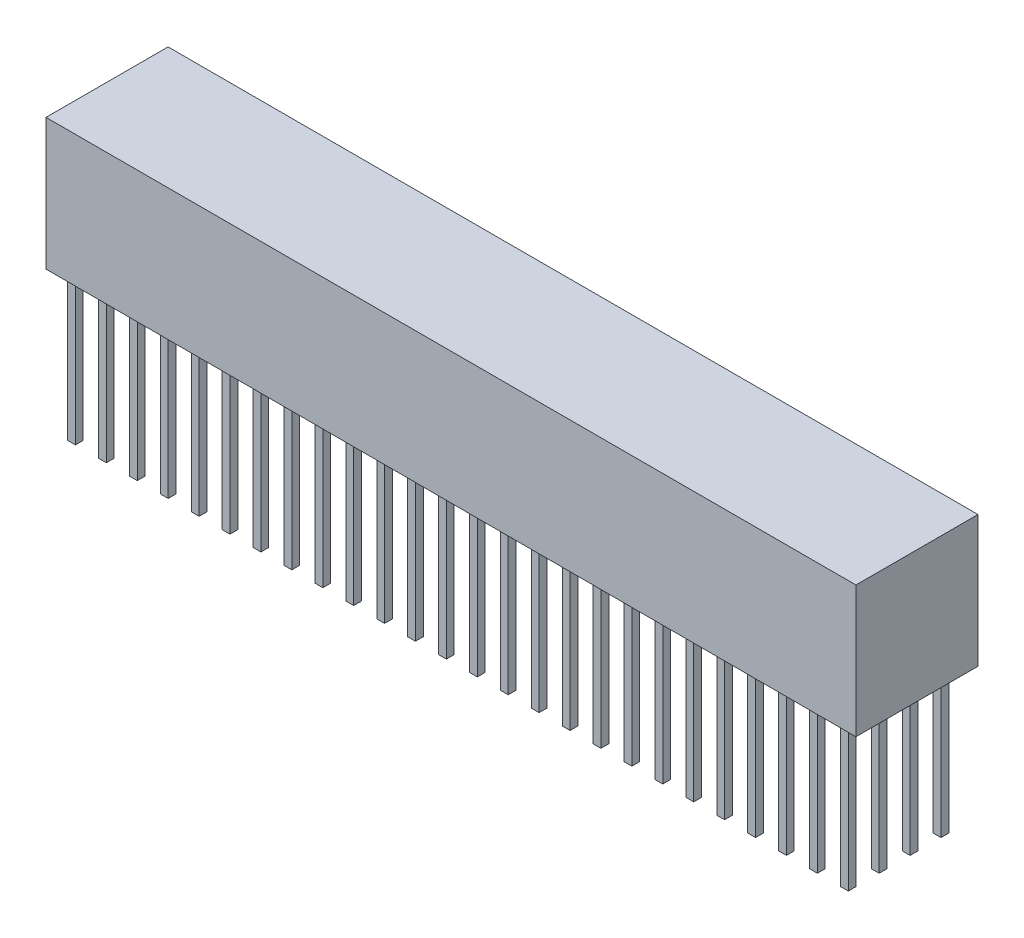
SolidWorks part; units mm, degrees
ref_plane "Front Plane" through (0, 0, 0) normal (0, 0, 1) x (1, 0, 0)
ref_plane "Top Plane" through (0, 0, 0) normal (0, 1, 0) x (1, 0, 0)
ref_plane "Right Plane" through (0, 0, 0) normal (1, 0, 0) x (0, 0, -1)
sketch "Sketch1" plane through (0, 0, 0) normal (0, 1, 0) x (1, 0, 0)
  line L1 (0, 0) -> (66.55, 0)
  line L2 (0, 0) -> (0, 10.03)
  line L3 (0, 10.03) -> (66.55, 10.03)
  line L4 (66.55, 0) -> (66.55, 10.03)
  dimension "D1" = 66.55
  dimension "D2" = 10.03
extrude "Boss-Extrude1" add sketch "Sketch1" along normal blind 10.8
sketch "Sketch2" plane through (0, 0, 0) normal (0, -1, 0) x (1, 0, 0)
  line L0 (0, 0) -> (66.55, 0) construction
  line L1 (0.89, -0.89) -> (1.53, -0.89)
  line L2 (0.89, -0.89) -> (0.89, -1.53)
  line L3 (0.89, -1.53) -> (1.53, -1.53)
  line L4 (1.53, -0.89) -> (1.53, -1.53)
  line L5 (0, -10.03) -> (0, 0) construction
  line L6 (3.43, -0.89) -> (3.43, -1.53)
  line L7 (3.43, -0.89) -> (4.07, -0.89)
  line L8 (4.07, -0.89) -> (4.07, -1.53)
  line L9 (3.43, -1.53) -> (4.07, -1.53)
  line L10 (5.97, -0.89) -> (5.97, -1.53)
  line L11 (5.97, -0.89) -> (6.61, -0.89)
  line L12 (6.61, -0.89) -> (6.61, -1.53)
  line L13 (5.97, -1.53) -> (6.61, -1.53)
  line L14 (8.51, -0.89) -> (8.51, -1.53)
  line L15 (8.51, -0.89) -> (9.15, -0.89)
  line L16 (9.15, -0.89) -> (9.15, -1.53)
  line L17 (8.51, -1.53) -> (9.15, -1.53)
  line L18 (11.05, -0.89) -> (11.05, -1.53)
  line L19 (11.05, -0.89) -> (11.69, -0.89)
  line L20 (11.69, -0.89) -> (11.69, -1.53)
  line L21 (11.05, -1.53) -> (11.69, -1.53)
  line L22 (13.59, -0.89) -> (13.59, -1.53)
  line L23 (13.59, -0.89) -> (14.23, -0.89)
  line L24 (14.23, -0.89) -> (14.23, -1.53)
  line L25 (13.59, -1.53) -> (14.23, -1.53)
  line L26 (16.13, -0.89) -> (16.13, -1.53)
  line L27 (16.13, -0.89) -> (16.77, -0.89)
  line L28 (16.77, -0.89) -> (16.77, -1.53)
  line L29 (16.13, -1.53) -> (16.77, -1.53)
  line L30 (18.67, -0.89) -> (18.67, -1.53)
  line L31 (18.67, -0.89) -> (19.31, -0.89)
  line L32 (19.31, -0.89) -> (19.31, -1.53)
  line L33 (18.67, -1.53) -> (19.31, -1.53)
  line L34 (21.21, -0.89) -> (21.21, -1.53)
  line L35 (21.21, -0.89) -> (21.85, -0.89)
  line L36 (21.85, -0.89) -> (21.85, -1.53)
  line L37 (21.21, -1.53) -> (21.85, -1.53)
  line L38 (23.75, -0.89) -> (23.75, -1.53)
  line L39 (23.75, -0.89) -> (24.39, -0.89)
  line L40 (24.39, -0.89) -> (24.39, -1.53)
  line L41 (23.75, -1.53) -> (24.39, -1.53)
  line L42 (26.29, -0.89) -> (26.29, -1.53)
  line L43 (26.29, -0.89) -> (26.93, -0.89)
  line L44 (26.93, -0.89) -> (26.93, -1.53)
  line L45 (26.29, -1.53) -> (26.93, -1.53)
  line L46 (28.83, -0.89) -> (28.83, -1.53)
  line L47 (28.83, -0.89) -> (29.47, -0.89)
  line L48 (29.47, -0.89) -> (29.47, -1.53)
  line L49 (28.83, -1.53) -> (29.47, -1.53)
  line L50 (31.37, -0.89) -> (31.37, -1.53)
  line L51 (31.37, -0.89) -> (32.01, -0.89)
  line L52 (32.01, -0.89) -> (32.01, -1.53)
  line L53 (31.37, -1.53) -> (32.01, -1.53)
  line L54 (33.91, -0.89) -> (33.91, -1.53)
  line L55 (33.91, -0.89) -> (34.55, -0.89)
  line L56 (34.55, -0.89) -> (34.55, -1.53)
  line L57 (33.91, -1.53) -> (34.55, -1.53)
  line L58 (36.45, -0.89) -> (36.45, -1.53)
  line L59 (36.45, -0.89) -> (37.09, -0.89)
  line L60 (37.09, -0.89) -> (37.09, -1.53)
  line L61 (36.45, -1.53) -> (37.09, -1.53)
  line L62 (38.99, -0.89) -> (38.99, -1.53)
  line L63 (38.99, -0.89) -> (39.63, -0.89)
  line L64 (39.63, -0.89) -> (39.63, -1.53)
  line L65 (38.99, -1.53) -> (39.63, -1.53)
  line L66 (41.53, -0.89) -> (41.53, -1.53)
  line L67 (41.53, -0.89) -> (42.17, -0.89)
  line L68 (42.17, -0.89) -> (42.17, -1.53)
  line L69 (41.53, -1.53) -> (42.17, -1.53)
  line L70 (44.07, -0.89) -> (44.07, -1.53)
  line L71 (44.07, -0.89) -> (44.71, -0.89)
  line L72 (44.71, -0.89) -> (44.71, -1.53)
  line L73 (44.07, -1.53) -> (44.71, -1.53)
  line L74 (46.61, -0.89) -> (46.61, -1.53)
  line L75 (46.61, -0.89) -> (47.25, -0.89)
  line L76 (47.25, -0.89) -> (47.25, -1.53)
  line L77 (46.61, -1.53) -> (47.25, -1.53)
  line L78 (49.15, -0.89) -> (49.15, -1.53)
  line L79 (49.15, -0.89) -> (49.79, -0.89)
  line L80 (49.79, -0.89) -> (49.79, -1.53)
  line L81 (49.15, -1.53) -> (49.79, -1.53)
  line L82 (51.69, -0.89) -> (51.69, -1.53)
  line L83 (51.69, -0.89) -> (52.33, -0.89)
  line L84 (52.33, -0.89) -> (52.33, -1.53)
  line L85 (51.69, -1.53) -> (52.33, -1.53)
  line L86 (54.23, -0.89) -> (54.23, -1.53)
  line L87 (54.23, -0.89) -> (54.87, -0.89)
  line L88 (54.87, -0.89) -> (54.87, -1.53)
  line L89 (54.23, -1.53) -> (54.87, -1.53)
  line L90 (56.77, -0.89) -> (56.77, -1.53)
  line L91 (56.77, -0.89) -> (57.41, -0.89)
  line L92 (57.41, -0.89) -> (57.41, -1.53)
  line L93 (56.77, -1.53) -> (57.41, -1.53)
  line L94 (59.31, -0.89) -> (59.31, -1.53)
  line L95 (59.31, -0.89) -> (59.95, -0.89)
  line L96 (59.95, -0.89) -> (59.95, -1.53)
  line L97 (59.31, -1.53) -> (59.95, -1.53)
  line L98 (61.85, -0.89) -> (61.85, -1.53)
  line L99 (61.85, -0.89) -> (62.49, -0.89)
  line L100 (62.49, -0.89) -> (62.49, -1.53)
  line L101 (61.85, -1.53) -> (62.49, -1.53)
  line L102 (3.43, -3.43) -> (3.43, -4.07)
  line L103 (3.43, -3.43) -> (4.07, -3.43)
  line L104 (4.07, -3.43) -> (4.07, -4.07)
  line L105 (3.43, -4.07) -> (4.07, -4.07)
  line L106 (5.97, -3.43) -> (5.97, -4.07)
  line L107 (5.97, -3.43) -> (6.61, -3.43)
  line L108 (6.61, -3.43) -> (6.61, -4.07)
  line L109 (5.97, -4.07) -> (6.61, -4.07)
  line L110 (8.51, -3.43) -> (8.51, -4.07)
  line L111 (8.51, -3.43) -> (9.15, -3.43)
  line L112 (9.15, -3.43) -> (9.15, -4.07)
  line L113 (8.51, -4.07) -> (9.15, -4.07)
  line L114 (11.05, -3.43) -> (11.05, -4.07)
  line L115 (11.05, -3.43) -> (11.69, -3.43)
  line L116 (11.69, -3.43) -> (11.69, -4.07)
  line L117 (11.05, -4.07) -> (11.69, -4.07)
  line L118 (13.59, -3.43) -> (13.59, -4.07)
  line L119 (13.59, -3.43) -> (14.23, -3.43)
  line L120 (14.23, -3.43) -> (14.23, -4.07)
  line L121 (13.59, -4.07) -> (14.23, -4.07)
  line L122 (16.13, -3.43) -> (16.13, -4.07)
  line L123 (16.13, -3.43) -> (16.77, -3.43)
  line L124 (16.77, -3.43) -> (16.77, -4.07)
  line L125 (16.13, -4.07) -> (16.77, -4.07)
  line L126 (18.67, -3.43) -> (18.67, -4.07)
  line L127 (18.67, -3.43) -> (19.31, -3.43)
  line L128 (19.31, -3.43) -> (19.31, -4.07)
  line L129 (18.67, -4.07) -> (19.31, -4.07)
  line L130 (21.21, -3.43) -> (21.21, -4.07)
  line L131 (21.21, -3.43) -> (21.85, -3.43)
  line L132 (21.85, -3.43) -> (21.85, -4.07)
  line L133 (21.21, -4.07) -> (21.85, -4.07)
  line L134 (23.75, -3.43) -> (23.75, -4.07)
  line L135 (23.75, -3.43) -> (24.39, -3.43)
  line L136 (24.39, -3.43) -> (24.39, -4.07)
  line L137 (23.75, -4.07) -> (24.39, -4.07)
  line L138 (26.29, -3.43) -> (26.29, -4.07)
  line L139 (26.29, -3.43) -> (26.93, -3.43)
  line L140 (26.93, -3.43) -> (26.93, -4.07)
  line L141 (26.29, -4.07) -> (26.93, -4.07)
  line L142 (28.83, -3.43) -> (28.83, -4.07)
  line L143 (28.83, -3.43) -> (29.47, -3.43)
  line L144 (29.47, -3.43) -> (29.47, -4.07)
  line L145 (28.83, -4.07) -> (29.47, -4.07)
  line L146 (31.37, -3.43) -> (31.37, -4.07)
  line L147 (31.37, -3.43) -> (32.01, -3.43)
  line L148 (32.01, -3.43) -> (32.01, -4.07)
  line L149 (31.37, -4.07) -> (32.01, -4.07)
  line L150 (33.91, -3.43) -> (33.91, -4.07)
  line L151 (33.91, -3.43) -> (34.55, -3.43)
  line L152 (34.55, -3.43) -> (34.55, -4.07)
  line L153 (33.91, -4.07) -> (34.55, -4.07)
  line L154 (36.45, -3.43) -> (36.45, -4.07)
  line L155 (36.45, -3.43) -> (37.09, -3.43)
  line L156 (37.09, -3.43) -> (37.09, -4.07)
  line L157 (36.45, -4.07) -> (37.09, -4.07)
  line L158 (38.99, -3.43) -> (38.99, -4.07)
  line L159 (38.99, -3.43) -> (39.63, -3.43)
  line L160 (39.63, -3.43) -> (39.63, -4.07)
  line L161 (38.99, -4.07) -> (39.63, -4.07)
  line L162 (41.53, -3.43) -> (41.53, -4.07)
  line L163 (41.53, -3.43) -> (42.17, -3.43)
  line L164 (42.17, -3.43) -> (42.17, -4.07)
  line L165 (41.53, -4.07) -> (42.17, -4.07)
  line L166 (44.07, -3.43) -> (44.07, -4.07)
  line L167 (44.07, -3.43) -> (44.71, -3.43)
  line L168 (44.71, -3.43) -> (44.71, -4.07)
  line L169 (44.07, -4.07) -> (44.71, -4.07)
  line L170 (46.61, -3.43) -> (46.61, -4.07)
  line L171 (46.61, -3.43) -> (47.25, -3.43)
  line L172 (47.25, -3.43) -> (47.25, -4.07)
  line L173 (46.61, -4.07) -> (47.25, -4.07)
  line L174 (49.15, -3.43) -> (49.15, -4.07)
  line L175 (49.15, -3.43) -> (49.79, -3.43)
  line L176 (49.79, -3.43) -> (49.79, -4.07)
  line L177 (49.15, -4.07) -> (49.79, -4.07)
  line L178 (51.69, -3.43) -> (51.69, -4.07)
  line L179 (51.69, -3.43) -> (52.33, -3.43)
  line L180 (52.33, -3.43) -> (52.33, -4.07)
  line L181 (51.69, -4.07) -> (52.33, -4.07)
  line L182 (54.23, -3.43) -> (54.23, -4.07)
  line L183 (54.23, -3.43) -> (54.87, -3.43)
  line L184 (54.87, -3.43) -> (54.87, -4.07)
  line L185 (54.23, -4.07) -> (54.87, -4.07)
  line L186 (56.77, -3.43) -> (56.77, -4.07)
  line L187 (56.77, -3.43) -> (57.41, -3.43)
  line L188 (57.41, -3.43) -> (57.41, -4.07)
  line L189 (56.77, -4.07) -> (57.41, -4.07)
  line L190 (59.31, -3.43) -> (59.31, -4.07)
  line L191 (59.31, -3.43) -> (59.95, -3.43)
  line L192 (59.95, -3.43) -> (59.95, -4.07)
  line L193 (59.31, -4.07) -> (59.95, -4.07)
  line L194 (61.85, -3.43) -> (61.85, -4.07)
  line L195 (61.85, -3.43) -> (62.49, -3.43)
  line L196 (62.49, -3.43) -> (62.49, -4.07)
  line L197 (61.85, -4.07) -> (62.49, -4.07)
  line L198 (3.43, -5.97) -> (3.43, -6.61)
  line L199 (3.43, -5.97) -> (4.07, -5.97)
  line L200 (4.07, -5.97) -> (4.07, -6.61)
  line L201 (3.43, -6.61) -> (4.07, -6.61)
  line L202 (5.97, -5.97) -> (5.97, -6.61)
  line L203 (5.97, -5.97) -> (6.61, -5.97)
  line L204 (6.61, -5.97) -> (6.61, -6.61)
  line L205 (5.97, -6.61) -> (6.61, -6.61)
  line L206 (8.51, -5.97) -> (8.51, -6.61)
  line L207 (8.51, -5.97) -> (9.15, -5.97)
  line L208 (9.15, -5.97) -> (9.15, -6.61)
  line L209 (8.51, -6.61) -> (9.15, -6.61)
  line L210 (11.05, -5.97) -> (11.05, -6.61)
  line L211 (11.05, -5.97) -> (11.69, -5.97)
  line L212 (11.69, -5.97) -> (11.69, -6.61)
  line L213 (11.05, -6.61) -> (11.69, -6.61)
  line L214 (13.59, -5.97) -> (13.59, -6.61)
  line L215 (13.59, -5.97) -> (14.23, -5.97)
  line L216 (14.23, -5.97) -> (14.23, -6.61)
  line L217 (13.59, -6.61) -> (14.23, -6.61)
  line L218 (16.13, -5.97) -> (16.13, -6.61)
  line L219 (16.13, -5.97) -> (16.77, -5.97)
  line L220 (16.77, -5.97) -> (16.77, -6.61)
  line L221 (16.13, -6.61) -> (16.77, -6.61)
  line L222 (18.67, -5.97) -> (18.67, -6.61)
  line L223 (18.67, -5.97) -> (19.31, -5.97)
  line L224 (19.31, -5.97) -> (19.31, -6.61)
  line L225 (18.67, -6.61) -> (19.31, -6.61)
  line L226 (21.21, -5.97) -> (21.21, -6.61)
  line L227 (21.21, -5.97) -> (21.85, -5.97)
  line L228 (21.85, -5.97) -> (21.85, -6.61)
  line L229 (21.21, -6.61) -> (21.85, -6.61)
  line L230 (23.75, -5.97) -> (23.75, -6.61)
  line L231 (23.75, -5.97) -> (24.39, -5.97)
  line L232 (24.39, -5.97) -> (24.39, -6.61)
  line L233 (23.75, -6.61) -> (24.39, -6.61)
  line L234 (26.29, -5.97) -> (26.29, -6.61)
  line L235 (26.29, -5.97) -> (26.93, -5.97)
  line L236 (26.93, -5.97) -> (26.93, -6.61)
  line L237 (26.29, -6.61) -> (26.93, -6.61)
  line L238 (28.83, -5.97) -> (28.83, -6.61)
  line L239 (28.83, -5.97) -> (29.47, -5.97)
  line L240 (29.47, -5.97) -> (29.47, -6.61)
  line L241 (28.83, -6.61) -> (29.47, -6.61)
  line L242 (31.37, -5.97) -> (31.37, -6.61)
  line L243 (31.37, -5.97) -> (32.01, -5.97)
  line L244 (32.01, -5.97) -> (32.01, -6.61)
  line L245 (31.37, -6.61) -> (32.01, -6.61)
  line L246 (33.91, -5.97) -> (33.91, -6.61)
  line L247 (33.91, -5.97) -> (34.55, -5.97)
  line L248 (34.55, -5.97) -> (34.55, -6.61)
  line L249 (33.91, -6.61) -> (34.55, -6.61)
  line L250 (36.45, -5.97) -> (36.45, -6.61)
  line L251 (36.45, -5.97) -> (37.09, -5.97)
  line L252 (37.09, -5.97) -> (37.09, -6.61)
  line L253 (36.45, -6.61) -> (37.09, -6.61)
  line L254 (38.99, -5.97) -> (38.99, -6.61)
  line L255 (38.99, -5.97) -> (39.63, -5.97)
  line L256 (39.63, -5.97) -> (39.63, -6.61)
  line L257 (38.99, -6.61) -> (39.63, -6.61)
  line L258 (41.53, -5.97) -> (41.53, -6.61)
  line L259 (41.53, -5.97) -> (42.17, -5.97)
  line L260 (42.17, -5.97) -> (42.17, -6.61)
  line L261 (41.53, -6.61) -> (42.17, -6.61)
  line L262 (44.07, -5.97) -> (44.07, -6.61)
  line L263 (44.07, -5.97) -> (44.71, -5.97)
  line L264 (44.71, -5.97) -> (44.71, -6.61)
  line L265 (44.07, -6.61) -> (44.71, -6.61)
  line L266 (46.61, -5.97) -> (46.61, -6.61)
  line L267 (46.61, -5.97) -> (47.25, -5.97)
  line L268 (47.25, -5.97) -> (47.25, -6.61)
  line L269 (46.61, -6.61) -> (47.25, -6.61)
  line L270 (49.15, -5.97) -> (49.15, -6.61)
  line L271 (49.15, -5.97) -> (49.79, -5.97)
  line L272 (49.79, -5.97) -> (49.79, -6.61)
  line L273 (49.15, -6.61) -> (49.79, -6.61)
  line L274 (51.69, -5.97) -> (51.69, -6.61)
  line L275 (51.69, -5.97) -> (52.33, -5.97)
  line L276 (52.33, -5.97) -> (52.33, -6.61)
  line L277 (51.69, -6.61) -> (52.33, -6.61)
  line L278 (54.23, -5.97) -> (54.23, -6.61)
  line L279 (54.23, -5.97) -> (54.87, -5.97)
  line L280 (54.87, -5.97) -> (54.87, -6.61)
  line L281 (54.23, -6.61) -> (54.87, -6.61)
  line L282 (56.77, -5.97) -> (56.77, -6.61)
  line L283 (56.77, -5.97) -> (57.41, -5.97)
  line L284 (57.41, -5.97) -> (57.41, -6.61)
  line L285 (56.77, -6.61) -> (57.41, -6.61)
  line L286 (59.31, -5.97) -> (59.31, -6.61)
  line L287 (59.31, -5.97) -> (59.95, -5.97)
  line L288 (59.95, -5.97) -> (59.95, -6.61)
  line L289 (59.31, -6.61) -> (59.95, -6.61)
  line L290 (61.85, -5.97) -> (61.85, -6.61)
  line L291 (61.85, -5.97) -> (62.49, -5.97)
  line L292 (62.49, -5.97) -> (62.49, -6.61)
  line L293 (61.85, -6.61) -> (62.49, -6.61)
  line L294 (3.43, -8.51) -> (3.43, -9.15)
  line L295 (3.43, -8.51) -> (4.07, -8.51)
  line L296 (4.07, -8.51) -> (4.07, -9.15)
  line L297 (3.43, -9.15) -> (4.07, -9.15)
  line L298 (5.97, -8.51) -> (5.97, -9.15)
  line L299 (5.97, -8.51) -> (6.61, -8.51)
  line L300 (6.61, -8.51) -> (6.61, -9.15)
  line L301 (5.97, -9.15) -> (6.61, -9.15)
  line L302 (8.51, -8.51) -> (8.51, -9.15)
  line L303 (8.51, -8.51) -> (9.15, -8.51)
  line L304 (9.15, -8.51) -> (9.15, -9.15)
  line L305 (8.51, -9.15) -> (9.15, -9.15)
  line L306 (11.05, -8.51) -> (11.05, -9.15)
  line L307 (11.05, -8.51) -> (11.69, -8.51)
  line L308 (11.69, -8.51) -> (11.69, -9.15)
  line L309 (11.05, -9.15) -> (11.69, -9.15)
  line L310 (13.59, -8.51) -> (13.59, -9.15)
  line L311 (13.59, -8.51) -> (14.23, -8.51)
  line L312 (14.23, -8.51) -> (14.23, -9.15)
  line L313 (13.59, -9.15) -> (14.23, -9.15)
  line L314 (16.13, -8.51) -> (16.13, -9.15)
  line L315 (16.13, -8.51) -> (16.77, -8.51)
  line L316 (16.77, -8.51) -> (16.77, -9.15)
  line L317 (16.13, -9.15) -> (16.77, -9.15)
  line L318 (18.67, -8.51) -> (18.67, -9.15)
  line L319 (18.67, -8.51) -> (19.31, -8.51)
  line L320 (19.31, -8.51) -> (19.31, -9.15)
  line L321 (18.67, -9.15) -> (19.31, -9.15)
  line L322 (21.21, -8.51) -> (21.21, -9.15)
  line L323 (21.21, -8.51) -> (21.85, -8.51)
  line L324 (21.85, -8.51) -> (21.85, -9.15)
  line L325 (21.21, -9.15) -> (21.85, -9.15)
  line L326 (23.75, -8.51) -> (23.75, -9.15)
  line L327 (23.75, -8.51) -> (24.39, -8.51)
  line L328 (24.39, -8.51) -> (24.39, -9.15)
  line L329 (23.75, -9.15) -> (24.39, -9.15)
  line L330 (26.29, -8.51) -> (26.29, -9.15)
  line L331 (26.29, -8.51) -> (26.93, -8.51)
  line L332 (26.93, -8.51) -> (26.93, -9.15)
  line L333 (26.29, -9.15) -> (26.93, -9.15)
  line L334 (28.83, -8.51) -> (28.83, -9.15)
  line L335 (28.83, -8.51) -> (29.47, -8.51)
  line L336 (29.47, -8.51) -> (29.47, -9.15)
  line L337 (28.83, -9.15) -> (29.47, -9.15)
  line L338 (31.37, -8.51) -> (31.37, -9.15)
  line L339 (31.37, -8.51) -> (32.01, -8.51)
  line L340 (32.01, -8.51) -> (32.01, -9.15)
  line L341 (31.37, -9.15) -> (32.01, -9.15)
  line L342 (33.91, -8.51) -> (33.91, -9.15)
  line L343 (33.91, -8.51) -> (34.55, -8.51)
  line L344 (34.55, -8.51) -> (34.55, -9.15)
  line L345 (33.91, -9.15) -> (34.55, -9.15)
  line L346 (36.45, -8.51) -> (36.45, -9.15)
  line L347 (36.45, -8.51) -> (37.09, -8.51)
  line L348 (37.09, -8.51) -> (37.09, -9.15)
  line L349 (36.45, -9.15) -> (37.09, -9.15)
  line L350 (38.99, -8.51) -> (38.99, -9.15)
  line L351 (38.99, -8.51) -> (39.63, -8.51)
  line L352 (39.63, -8.51) -> (39.63, -9.15)
  line L353 (38.99, -9.15) -> (39.63, -9.15)
  line L354 (41.53, -8.51) -> (41.53, -9.15)
  line L355 (41.53, -8.51) -> (42.17, -8.51)
  line L356 (42.17, -8.51) -> (42.17, -9.15)
  line L357 (41.53, -9.15) -> (42.17, -9.15)
  line L358 (44.07, -8.51) -> (44.07, -9.15)
  line L359 (44.07, -8.51) -> (44.71, -8.51)
  line L360 (44.71, -8.51) -> (44.71, -9.15)
  line L361 (44.07, -9.15) -> (44.71, -9.15)
  line L362 (46.61, -8.51) -> (46.61, -9.15)
  line L363 (46.61, -8.51) -> (47.25, -8.51)
  line L364 (47.25, -8.51) -> (47.25, -9.15)
  line L365 (46.61, -9.15) -> (47.25, -9.15)
  line L366 (49.15, -8.51) -> (49.15, -9.15)
  line L367 (49.15, -8.51) -> (49.79, -8.51)
  line L368 (49.79, -8.51) -> (49.79, -9.15)
  line L369 (49.15, -9.15) -> (49.79, -9.15)
  line L370 (51.69, -8.51) -> (51.69, -9.15)
  line L371 (51.69, -8.51) -> (52.33, -8.51)
  line L372 (52.33, -8.51) -> (52.33, -9.15)
  line L373 (51.69, -9.15) -> (52.33, -9.15)
  line L374 (54.23, -8.51) -> (54.23, -9.15)
  line L375 (54.23, -8.51) -> (54.87, -8.51)
  line L376 (54.87, -8.51) -> (54.87, -9.15)
  line L377 (54.23, -9.15) -> (54.87, -9.15)
  line L378 (56.77, -8.51) -> (56.77, -9.15)
  line L379 (56.77, -8.51) -> (57.41, -8.51)
  line L380 (57.41, -8.51) -> (57.41, -9.15)
  line L381 (56.77, -9.15) -> (57.41, -9.15)
  line L382 (59.31, -8.51) -> (59.31, -9.15)
  line L383 (59.31, -8.51) -> (59.95, -8.51)
  line L384 (59.95, -8.51) -> (59.95, -9.15)
  line L385 (59.31, -9.15) -> (59.95, -9.15)
  line L386 (61.85, -8.51) -> (61.85, -9.15)
  line L387 (61.85, -8.51) -> (62.49, -8.51)
  line L388 (62.49, -8.51) -> (62.49, -9.15)
  line L389 (61.85, -9.15) -> (62.49, -9.15)
  line L390 (0.89, -3.43) -> (0.89, -4.07)
  line L391 (0.89, -3.43) -> (1.53, -3.43)
  line L392 (1.53, -3.43) -> (1.53, -4.07)
  line L393 (0.89, -4.07) -> (1.53, -4.07)
  line L394 (0.89, -5.97) -> (0.89, -6.61)
  line L395 (0.89, -5.97) -> (1.53, -5.97)
  line L396 (1.53, -5.97) -> (1.53, -6.61)
  line L397 (0.89, -6.61) -> (1.53, -6.61)
  line L398 (0.89, -8.51) -> (0.89, -9.15)
  line L399 (0.89, -8.51) -> (1.53, -8.51)
  line L400 (1.53, -8.51) -> (1.53, -9.15)
  line L401 (0.89, -9.15) -> (1.53, -9.15)
  line L402 (64.39, -0.89) -> (64.39, -1.53)
  line L403 (64.39, -0.89) -> (65.03, -0.89)
  line L404 (65.03, -0.89) -> (65.03, -1.53)
  line L405 (64.39, -1.53) -> (65.03, -1.53)
  line L406 (64.39, -3.43) -> (64.39, -4.07)
  line L407 (64.39, -3.43) -> (65.03, -3.43)
  line L408 (65.03, -3.43) -> (65.03, -4.07)
  line L409 (64.39, -4.07) -> (65.03, -4.07)
  line L410 (64.39, -5.97) -> (64.39, -6.61)
  line L411 (64.39, -5.97) -> (65.03, -5.97)
  line L412 (65.03, -5.97) -> (65.03, -6.61)
  line L413 (64.39, -6.61) -> (65.03, -6.61)
  line L414 (64.39, -8.51) -> (64.39, -9.15)
  line L415 (64.39, -8.51) -> (65.03, -8.51)
  line L416 (65.03, -8.51) -> (65.03, -9.15)
  line L417 (64.39, -9.15) -> (65.03, -9.15)
  dimension "D1" = 0.64
  dimension "D2" = 0.64
  dimension "D3" = 0.89
  dimension "D4" = 0.89
  dimension "D5" = 26
  dimension "D6" = 4
extrude "Boss-Extrude2" add sketch "Sketch2" along normal blind 12.19
